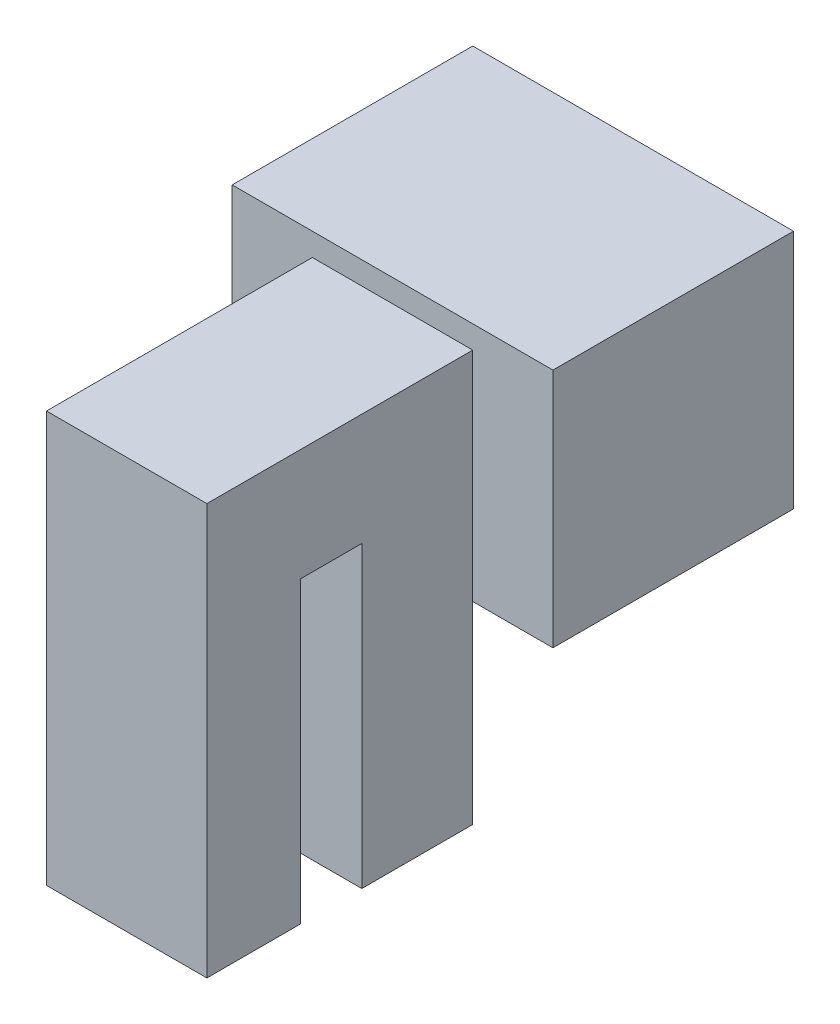
SolidWorks part; units mm, degrees
ref_plane "Front" through (0, 0, 0) normal (0, 0, 1) x (1, 0, 0)
ref_plane "Top" through (0, 0, 0) normal (0, 1, 0) x (1, 0, 0)
ref_plane "Right" through (0, 0, 0) normal (1, 0, 0) x (0, 0, -1)
sketch "Esquisse1" plane through (0, 0, 0) normal (0, 0, 1) x (1, 0, 0)
  line L1 (0, 0) -> (-40, 0)
  line L2 (0, 0) -> (0, 30)
  line L3 (0, 30) -> (-40, 30)
  line L4 (-40, 0) -> (-40, 30)
  dimension "D1" = 40
  dimension "D2" = 30
extrude "Boss.-Extru.1" add sketch "Esquisse1" along normal blind 30
sketch "Esquisse2" plane through (-40, 0, 0) normal (-1, 0, 0) x (0, 0, 1)
  line L0 (30, 30) -> (30, 0) construction
  line L1 (30, 27.1582) -> (63.1562, 27.1582)
  line L2 (30, 27.1582) -> (30, -24.0798)
  line L3 (30, -24.0798) -> (43.8334, -24.0798)
  line L4 (63.1562, 27.1582) -> (63.1562, -24.0798)
  line L5 (51.5046, -24.0798) -> (63.1562, -24.0798)
  line L7 (43.8334, -24.0798) -> (43.8334, 13.1907)
  line L8 (43.8334, 13.1907) -> (51.5046, 13.1907)
  line L9 (51.5046, -24.0798) -> (51.5046, 13.1907)
extrude "Boss.-Extru.2" add sketch "Esquisse2" against normal blind 20 from offset 10
